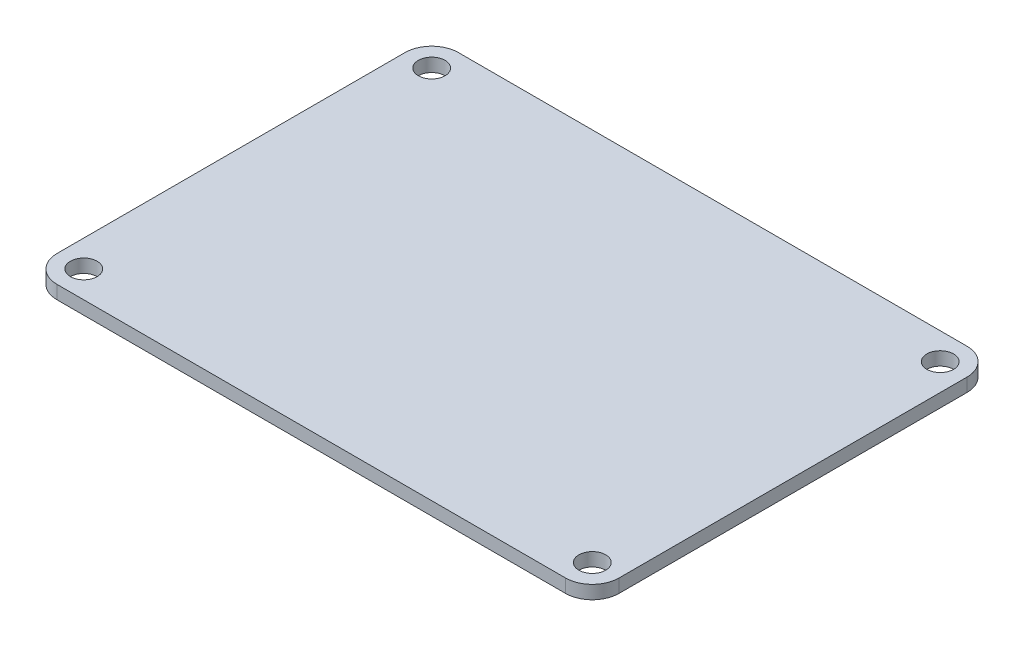
SolidWorks part; units mm, degrees
ref_plane "Спереди" through (0, 0, 0) normal (0, 0, 1) x (1, 0, 0)
ref_plane "Сверху" through (0, 0, 0) normal (0, 1, 0) x (1, 0, 0)
ref_plane "Справа" through (0, 0, 0) normal (1, 0, 0) x (0, 0, -1)
sketch "Эскиз1" plane through (0, 0, 0) normal (0, 1, 0) x (1, 0, 0)
  line L1 (31.5, -22.5) -> (-31.5, -22.5)
  line L2 (31.5, -22.5) -> (31.5, 22.5)
  line L3 (31.5, 22.5) -> (-31.5, 22.5)
  line L4 (-31.5, -22.5) -> (-31.5, 22.5)
  line L5 (31.5, -22.5) -> (-31.5, 22.5) construction
  line L6 (31.5, 22.5) -> (-31.5, -22.5) construction
  point P0 (0, 0)
  dimension "D1" = 63
  dimension "D2" = 45
extrude "Бобышка-Вытянуть1" add sketch "Эскиз1" along normal blind 1.5
fillet "Скругление1" radius 3 4 edges at (-31.5, 0.75, 22.5) (-31.5, 0.75, -22.5) (31.5, 0.75, -22.5) (31.5, 0.75, 22.5)
sketch "Эскиз2" plane through (0, 1.5, 0) normal (0, 1, 0) x (1, 0, 0)
  line L0 (28.5, 22.5) -> (-28.5, 22.5) construction
  line L1 (28.5, -19.5) -> (-28.5, -19.5) construction
  line L2 (28.5, -19.5) -> (28.5, 19.5) construction
  line L3 (28.5, 19.5) -> (-28.5, 19.5) construction
  line L4 (-28.5, -19.5) -> (-28.5, 19.5) construction
  line L5 (28.5, -19.5) -> (-28.5, 19.5) construction
  line L6 (28.5, 19.5) -> (-28.5, -19.5) construction
  line L7 (-31.5, 19.5) -> (-31.5, -19.5) construction
  circle A0 centre (-28.5, 19.5) radius 1.5
  circle A1 centre (28.5, 19.5) radius 1.5
  circle A2 centre (28.5, -19.5) radius 1.5
  circle A3 centre (-28.5, -19.5) radius 1.5
  point P0 (0, 0)
  dimension "D3" = 3
  dimension "D1" = 3
  dimension "D2" = 3
extrude "Вырез-Вытянуть1" cut sketch "Эскиз2" against normal through all
